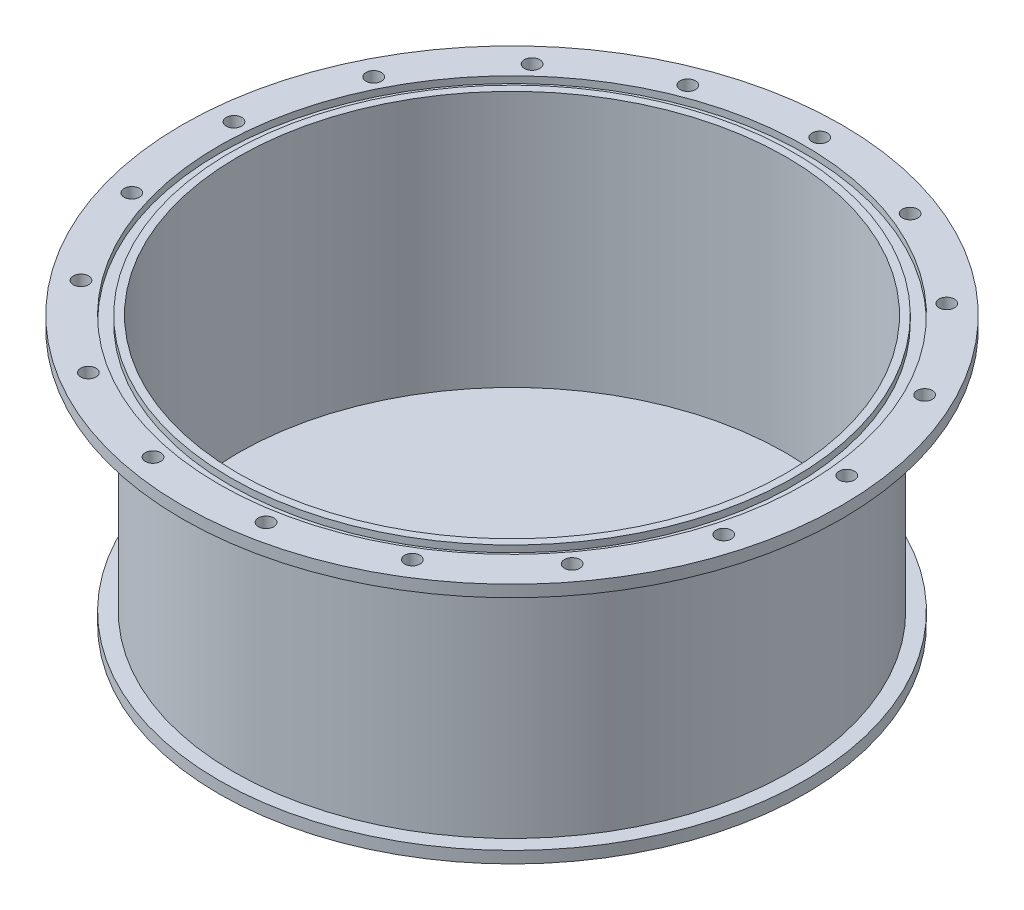
SolidWorks part; units mm, degrees
material "Plain Carbon Steel"
ref_plane "Front Plane" through (0, 0, 0) normal (0, 0, 1) x (1, 0, 0)
ref_plane "Top Plane" through (0, 0, 0) normal (0, 1, 0) x (1, 0, 0)
ref_plane "Right Plane" through (0, 0, 0) normal (1, 0, 0) x (0, 0, -1)
sketch "Sketch1" plane through (0, 0, 0) normal (0, 1, 0) x (1, 0, 0)
  circle A0 centre (0, 0) radius 200
extrude "Boss-Extrude1" add sketch "Sketch1" against normal blind 8
sketch "Sketch2" plane through (0, 0, 0) normal (0, 1, 0) x (1, 0, 0)
  circle A0 centre (0, 0) radius 190
extrude "Boss-Extrude2" add sketch "Sketch2" along normal blind 175
sketch "Sketch3" plane through (0, 175, 0) normal (0, 1, 0) x (1, 0, 0)
  circle A0 centre (0, 0) radius 225
extrude "Boss-Extrude3" add sketch "Sketch3" against normal blind 8
sketch "Sketch4" plane through (0, 175, 0) normal (0, 1, 0) x (1, 0, 0)
  circle A0 centre (0, 0) radius 187
extrude "Cut-Extrude1" cut sketch "Sketch4" against normal blind 175
sketch "Sketch5" plane through (0, 175, 0) normal (0, 1, 0) x (1, 0, 0)
  circle A0 centre (0, 0) radius 192.2
  circle A1 centre (0, 0) radius 200
extrude "Cut-Extrude2" cut sketch "Sketch5" against normal blind 4.6
sketch "Sketch6" plane through (0, 175, 0) normal (0, 1, 0) x (1, 0, 0)
  circle A0 centre (0, 210) radius 5.25
extrude "Cut-Extrude3" cut sketch "Sketch6" against normal blind 10
pattern_circular "CirPattern1" count 17 over 360 about axis through (0, 0, 0) along (0, 1, 0) of "Cut-Extrude3"
